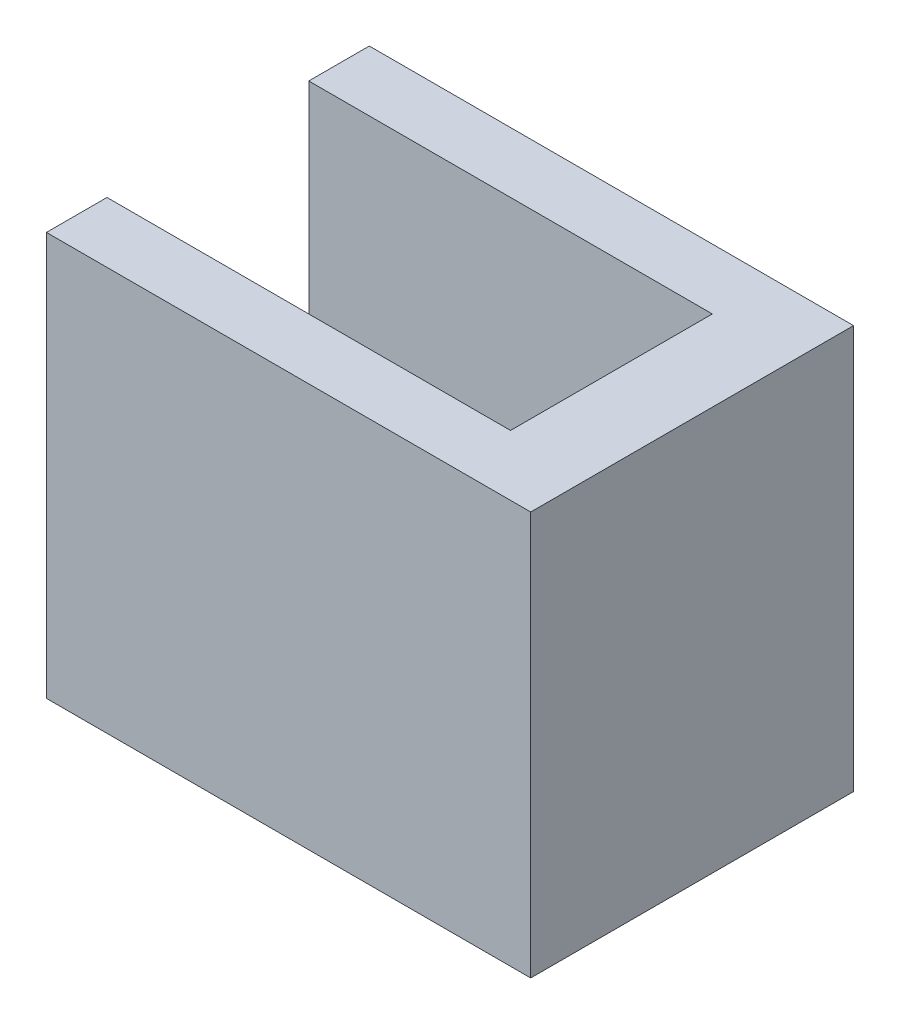
SolidWorks part; units mm, degrees
ref_plane "Front Plane" through (0, 0, 0) normal (0, 0, 1) x (1, 0, 0)
ref_plane "Top Plane" through (0, 0, 0) normal (0, 1, 0) x (1, 0, 0)
ref_plane "Right Plane" through (0, 0, 0) normal (1, 0, 0) x (0, 0, -1)
sketch "Sketch1" plane through (0, 0, 0) normal (0, 1, 0) x (1, 0, 0)
  line L0 (-6.7391, -1.1522) -> (-6.7391, -2.6522)
  line L1 (-6.7391, 5.3478) -> (5.2609, 5.3478)
  line L2 (-6.7391, 5.3478) -> (-6.7391, 3.8478)
  line L3 (-6.7391, -2.6522) -> (5.2609, -2.6522)
  line L4 (5.2609, 5.3478) -> (5.2609, -2.6522)
  line L5 (-6.7391, 3.8478) -> (3.2609, 3.8478)
  line L7 (-6.7391, -1.1522) -> (3.2609, -1.1522)
  line L8 (3.2609, 3.8478) -> (3.2609, -1.1522)
  point P8 (3.2609, 1.3478)
  point P9 (5.2609, 1.3478)
  point P10 (0, 0)
  dimension "D1" = 5
  dimension "D2" = 8
  dimension "D3" = 2
  dimension "D4" = 10
extrude "Boss-Extrude1" add sketch "Sketch1" along normal blind 10
